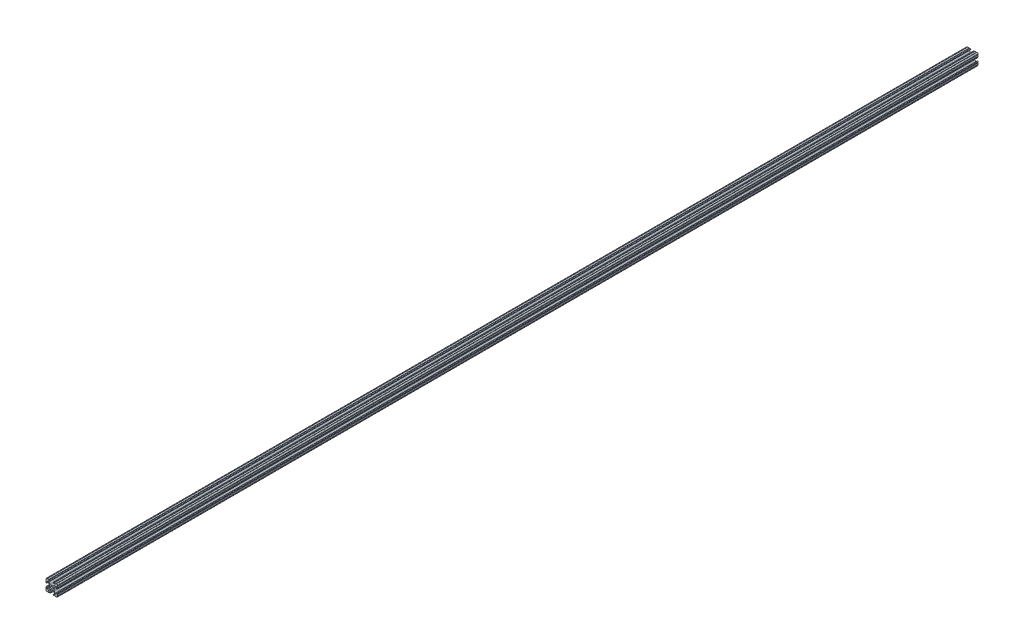
SolidWorks part; units mm, degrees
ref_plane "Front Plane" through (0, 0, 0) normal (0, 0, 1) x (1, 0, 0)
ref_plane "Top Plane" through (0, 0, 0) normal (0, 1, 0) x (1, 0, 0)
ref_plane "Right Plane" through (0, 0, 0) normal (1, 0, 0) x (0, 0, -1)
sketch "Sketch1" plane through (0, 0, 0) normal (0, 0, 1) x (1, 0, 0)
  line L0 (-7.207, 8.7244) -> (-3.8983, 5.4232)
  line L1 (-4.2875, 10.4902) -> (-6.4768, 10.4902)
  line L2 (-3.2385, 11.651) -> (-3.2385, 11.5392)
  line L3 (-5.3171, 12.7) -> (-4.2875, 12.7)
  line L4 (0, 13.4005) -> (0, -14.8534) construction
  line L5 (12.7, 0) -> (-13.9989, 0) construction
  line L6 (-9.5504, 12.7) -> (-6.3331, 12.7)
  line L7 (-12.7, 6.3331) -> (-12.7, 9.5504)
  line L8 (-12.7, 4.2875) -> (-12.7, 5.3171)
  line L9 (-11.5392, 3.2385) -> (-11.651, 3.2385)
  line L10 (-10.4902, 6.4021) -> (-10.4902, 4.2875)
  line L11 (-5.441, 3.8408) -> (-8.7371, 7.1294)
  line L12 (-4.5085, -1.5932) -> (-4.5085, 1.5932)
  line L13 (-1.7093, -4.4958) -> (1.7093, -4.4958)
  line L14 (3.9523, -5.4237) -> (7.1797, -8.6452)
  line L15 (6.4164, -10.4902) -> (4.2875, -10.4902)
  line L16 (3.2385, -11.5392) -> (3.2385, -11.651)
  line L17 (4.2875, -12.7) -> (5.3171, -12.7)
  line L18 (6.3331, -12.7) -> (9.5504, -12.7)
  line L19 (12.7, -9.5504) -> (12.7, -6.3331)
  line L20 (12.7, -5.3171) -> (12.7, -4.2875)
  line L21 (11.651, -3.2385) -> (11.5392, -3.2385)
  line L22 (10.4902, -4.2875) -> (10.4902, -6.4021)
  line L23 (8.7371, -7.1294) -> (5.441, -3.8408)
  line L24 (4.5085, -1.5932) -> (4.5085, 1.5932)
  line L25 (5.441, 3.8408) -> (8.7371, 7.1294)
  line L26 (10.4902, 6.4021) -> (10.4902, 4.2875)
  line L27 (11.5392, 3.2385) -> (11.651, 3.2385)
  line L28 (12.7, 4.2875) -> (12.7, 5.3171)
  line L29 (12.7, 6.3331) -> (12.7, 9.5504)
  line L30 (9.5504, 12.7) -> (6.3331, 12.7)
  line L31 (5.3171, 12.7) -> (4.2875, 12.7)
  line L32 (3.2385, 11.651) -> (3.2385, 11.5392)
  line L33 (4.2875, 10.4902) -> (6.4768, 10.4902)
  line L34 (7.207, 8.7244) -> (3.8983, 5.4232)
  line L35 (1.6558, 4.4958) -> (-1.6558, 4.4958)
  line L36 (-8.7371, -7.1294) -> (-5.441, -3.8408)
  line L37 (-10.4902, -4.2875) -> (-10.4902, -6.4021)
  line L38 (-11.651, -3.2385) -> (-11.5392, -3.2385)
  line L39 (-12.7, -5.3171) -> (-12.7, -4.2875)
  line L40 (-12.7, -9.5504) -> (-12.7, -6.3331)
  line L41 (-6.3331, -12.7) -> (-9.5504, -12.7)
  line L42 (-4.2875, -12.7) -> (-5.3171, -12.7)
  line L43 (-3.2385, -11.5392) -> (-3.2385, -11.651)
  line L44 (-6.4164, -10.4902) -> (-4.2875, -10.4902)
  line L45 (-3.9523, -5.4237) -> (-7.1797, -8.6452)
  arc A0 (-7.207, 8.7244) -> (-6.4768, 10.4902) centre (-6.4768, 9.4563) cw
  arc A1 (-3.2385, 11.5392) -> (-4.2875, 10.4902) centre (-4.2875, 11.5392) cw
  arc A2 (-4.2875, 12.7) -> (-3.2385, 11.651) centre (-4.2875, 11.651) cw
  arc A3 (-5.3171, 12.7) -> (-6.3331, 12.7) centre (-5.8251, 12.7) cw
  arc A4 (-9.5504, 12.7) -> (-10.5664, 12.6998) centre (-10.0584, 12.7) cw
  arc A5 (-12.6998, 10.5664) -> (-10.5664, 12.6998) centre (-10.5918, 10.5918) cw
  arc A6 (-12.6998, 10.5664) -> (-12.7, 9.5504) centre (-12.7, 10.0584) cw
  arc A7 (-12.7, 6.3331) -> (-12.7, 5.3171) centre (-12.7, 5.8251) cw
  arc A8 (-11.651, 3.2385) -> (-12.7, 4.2875) centre (-11.651, 4.2875) cw
  arc A9 (-10.4902, 4.2875) -> (-11.5392, 3.2385) centre (-11.5392, 4.2875) cw
  circle A10 centre (0, 0) radius 2.6035
  arc A11 (-10.4902, 6.4021) -> (-8.7371, 7.1294) centre (-9.4628, 6.4021) cw
  arc A12 (-5.441, 3.8408) -> (-4.5085, 1.5932) centre (-7.6835, 1.5932) cw
  arc A13 (-4.5085, -1.5932) -> (-5.441, -3.8408) centre (-7.6835, -1.5932) cw
  arc A14 (-8.7371, -7.1294) -> (-10.4902, -6.4021) centre (-9.4628, -6.4021) cw
  arc A15 (-1.7093, -4.4958) -> (-3.9523, -5.4237) centre (-1.7093, -7.6708) ccw
  arc A16 (3.9523, -5.4237) -> (1.7093, -4.4958) centre (1.7093, -7.6708) ccw
  arc A17 (6.4164, -10.4902) -> (7.1797, -8.6452) centre (6.4164, -9.4098) ccw
  arc A18 (4.2875, -10.4902) -> (3.2385, -11.5392) centre (4.2875, -11.5392) ccw
  arc A19 (3.2385, -11.651) -> (4.2875, -12.7) centre (4.2875, -11.651) ccw
  arc A20 (6.3331, -12.7) -> (5.3171, -12.7) centre (5.8251, -12.7) ccw
  arc A21 (10.5664, -12.6998) -> (9.5504, -12.7) centre (10.0584, -12.7) ccw
  arc A22 (10.5664, -12.6998) -> (12.6998, -10.5664) centre (10.5918, -10.5918) ccw
  arc A23 (12.7, -9.5504) -> (12.6998, -10.5664) centre (12.7, -10.0584) ccw
  arc A24 (12.7, -5.3171) -> (12.7, -6.3331) centre (12.7, -5.8251) ccw
  arc A25 (12.7, -4.2875) -> (11.651, -3.2385) centre (11.651, -4.2875) ccw
  arc A26 (11.5392, -3.2385) -> (10.4902, -4.2875) centre (11.5392, -4.2875) ccw
  arc A27 (8.7371, -7.1294) -> (10.4902, -6.4021) centre (9.4628, -6.4021) ccw
  arc A28 (4.5085, -1.5932) -> (5.441, -3.8408) centre (7.6835, -1.5932) ccw
  arc A29 (5.441, 3.8408) -> (4.5085, 1.5932) centre (7.6835, 1.5932) ccw
  arc A30 (10.4902, 6.4021) -> (8.7371, 7.1294) centre (9.4628, 6.4021) ccw
  arc A31 (10.4902, 4.2875) -> (11.5392, 3.2385) centre (11.5392, 4.2875) ccw
  arc A32 (11.651, 3.2385) -> (12.7, 4.2875) centre (11.651, 4.2875) ccw
  arc A33 (12.7, 6.3331) -> (12.7, 5.3171) centre (12.7, 5.8251) ccw
  arc A34 (12.6998, 10.5664) -> (12.7, 9.5504) centre (12.7, 10.0584) ccw
  arc A35 (12.6998, 10.5664) -> (10.5664, 12.6998) centre (10.5918, 10.5918) ccw
  arc A36 (9.5504, 12.7) -> (10.5664, 12.6998) centre (10.0584, 12.7) ccw
  arc A37 (5.3171, 12.7) -> (6.3331, 12.7) centre (5.8251, 12.7) ccw
  arc A38 (4.2875, 12.7) -> (3.2385, 11.651) centre (4.2875, 11.651) ccw
  arc A39 (3.2385, 11.5392) -> (4.2875, 10.4902) centre (4.2875, 11.5392) ccw
  arc A40 (7.207, 8.7244) -> (6.4768, 10.4902) centre (6.4768, 9.4563) ccw
  arc A41 (1.6558, 4.4958) -> (3.8983, 5.4232) centre (1.6558, 7.6708) ccw
  arc A42 (-1.6558, 4.4958) -> (-3.8983, 5.4232) centre (-1.6558, 7.6708) cw
  arc A43 (-11.5392, -3.2385) -> (-10.4902, -4.2875) centre (-11.5392, -4.2875) cw
  arc A44 (-12.7, -4.2875) -> (-11.651, -3.2385) centre (-11.651, -4.2875) cw
  arc A45 (-12.7, -5.3171) -> (-12.7, -6.3331) centre (-12.7, -5.8251) cw
  arc A46 (-12.7, -9.5504) -> (-12.6998, -10.5664) centre (-12.7, -10.0584) cw
  arc A47 (-10.5664, -12.6998) -> (-12.6998, -10.5664) centre (-10.5918, -10.5918) cw
  arc A48 (-10.5664, -12.6998) -> (-9.5504, -12.7) centre (-10.0584, -12.7) cw
  arc A49 (-6.3331, -12.7) -> (-5.3171, -12.7) centre (-5.8251, -12.7) cw
  arc A50 (-3.2385, -11.651) -> (-4.2875, -12.7) centre (-4.2875, -11.651) cw
  arc A51 (-4.2875, -10.4902) -> (-3.2385, -11.5392) centre (-4.2875, -11.5392) cw
  arc A52 (-6.4164, -10.4902) -> (-7.1797, -8.6452) centre (-6.4164, -9.4098) cw
  dimension "D1" = 5.207
  dimension "D9" = 14.859
  dimension "D2" = 25.4
  dimension "D3" = 12.7
  dimension "D4" = 6.477
  dimension "D5" = 8.2042
  dimension "D6" = 9.017
  dimension "D8" = 2.2098
  dimension "D10" = 2.2098
extrude "Extrude1" add sketch "Sketch1" against normal blind 2032
